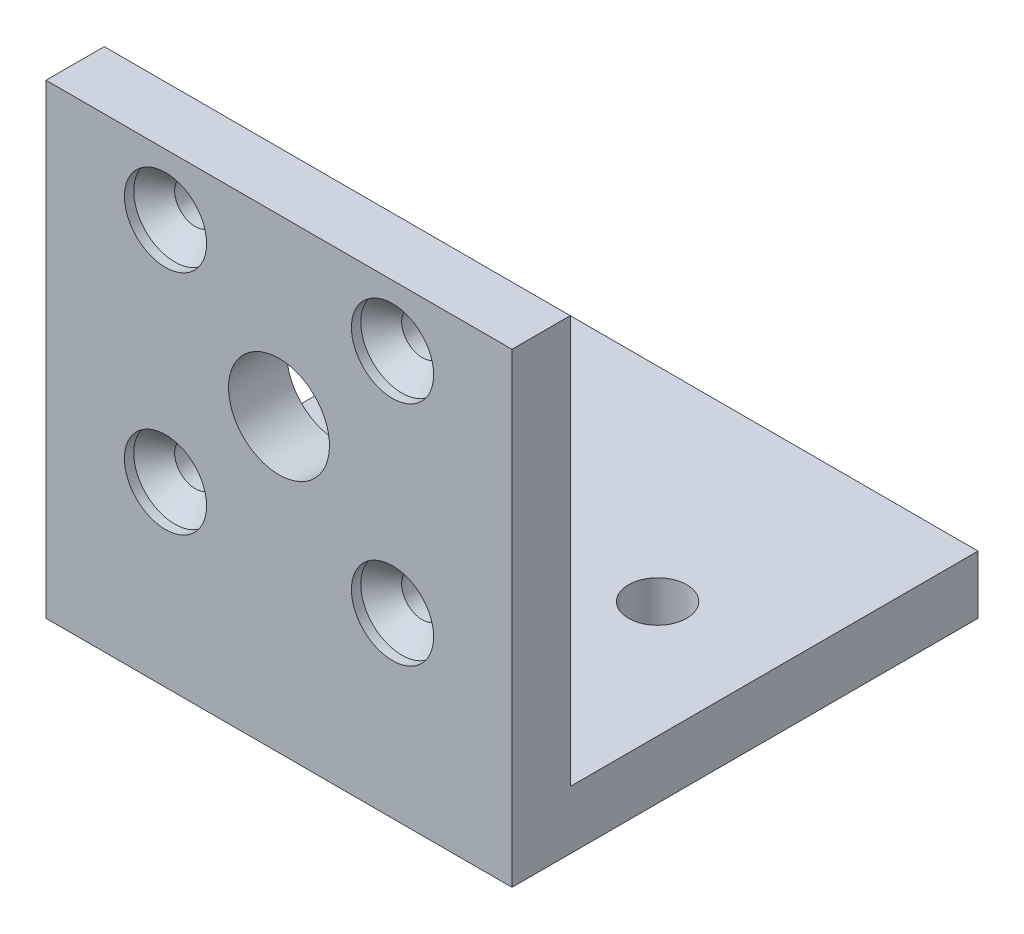
SolidWorks part; units mm, degrees
ref_plane "Front Plane" through (0, 0, 0) normal (0, 0, 1) x (1, 0, 0)
ref_plane "Top Plane" through (0, 0, 0) normal (0, 1, 0) x (1, 0, 0)
ref_plane "Right Plane" through (0, 0, 0) normal (1, 0, 0) x (0, 0, -1)
sketch "Sketch1" plane through (0, 0, 0) normal (1, 0, 0) x (0, 0, -1)
  line L0 (0, 0) -> (0, -44.45)
  line L1 (0, -44.45) -> (44.45, -44.45)
  line L2 (-6.35, 0) -> (-6.35, -50.8)
  line L3 (-6.35, -50.8) -> (44.45, -50.8)
  line L4 (-6.35, 0) -> (0, 0)
  line L5 (44.45, -44.45) -> (44.45, -50.8)
  dimension "D2" = 50.8
  dimension "D3" = 50.8
  dimension "D1" = 6.35
extrude "Boss-Extrude1" add sketch "Sketch1" along normal blind 50.8
sketch "Sketch2" plane through (0, 0, 0) normal (0, 0, -1) x (-1, 0, 0)
  line L1 (-50.8, 0) -> (0, 0) construction
  line L2 (-13.0256, -6.6756) -> (-37.7744, -6.6756) construction
  line L3 (-50.8, -44.45) -> (-50.8, 0) construction
  circle A0 centre (-13.0256, -6.6756) radius 2.25
  circle A1 centre (-13.0256, -31.4244) radius 2.25
  circle A2 centre (-37.7744, -31.4244) radius 2.25
  circle A3 centre (-37.7744, -6.6756) radius 2.25
  circle A4 centre (-25.4, -19.05) radius 5.5
  point P3 (-50.8, -22.225)
  point P12 (-25.4, -19.05)
  dimension "D1" = 17.5
  dimension "D2" = 4.5
  dimension "D7" = 11
  dimension "D4" = 25.4
  dimension "D5" = 19.05
  dimension "D6" = 0
  dimension "D3" = 4
extrude "Cut-Extrude1" cut sketch "Sketch2" against normal up to next
sketch "Sketch4" plane through (0, -44.45, 0) normal (0, 1, 0) x (1, 0, 0)
  line L0 (0, 44.45) -> (0, 0) construction
  line L1 (50.8, 44.45) -> (0, 44.45) construction
  line L2 (50.8, 44.45) -> (50.8, 0) construction
  circle A0 centre (12.7, 22.225) radius 3.175
  circle A1 centre (38.1, 22.225) radius 3.175
  dimension "D1" = 6.35
  dimension "D2" = 6.35
  dimension "D3" = 12.7
  dimension "D4" = 22.225
  dimension "D5" = 22.225
  dimension "D6" = 12.7
extrude "Cut-Extrude2" cut sketch "Sketch4" against normal up to next
hole_wizard "CSK for M4 SFHCS1" positions "Sketch6" profile "Sketch5" countersink size "M4" standard "ANSI Metric" end condition through all
sketch "Sketch6" plane through (0, 0, 6.35) normal (0, 0, 1) x (1, 0, 0)
  point P0 (13.0256, -6.6756)
  point P3 (37.7744, -6.6756)
  point P6 (37.7744, -31.4244)
  point P9 (13.0256, -31.4244)
sketch "Sketch5" plane through (13.0256, -6.6756, 6.35) normal (1, 0, 0) x (0, -1, 0)
  line L0 (0, 0) -> (0, 50.8)
  line L1 (0, 50.8) -> (2.15, 50.8)
  line L2 (2.15, 50.8) -> (2.15, 3.346)
  line L3 (2.15, 3.346) -> (4.48, 1.016)
  line L4 (4.48, 1.016) -> (4.48, 0)
  line L6 (4.48, 0) -> (0, 0)
  line L7 (-2.15, 3.346) -> (-4.48, 1.016) construction
  line L11 (0, -6.35) -> (0, 107.95) construction
  dimension "Thru Hole Dia." = 4.3
  dimension "Thru Hole Depth" = 50.8
  dimension "C'Sink Dia." = 8.96
  dimension "C'Sink Angle" = 90
  dimension "Head Clearance" = 1.016
